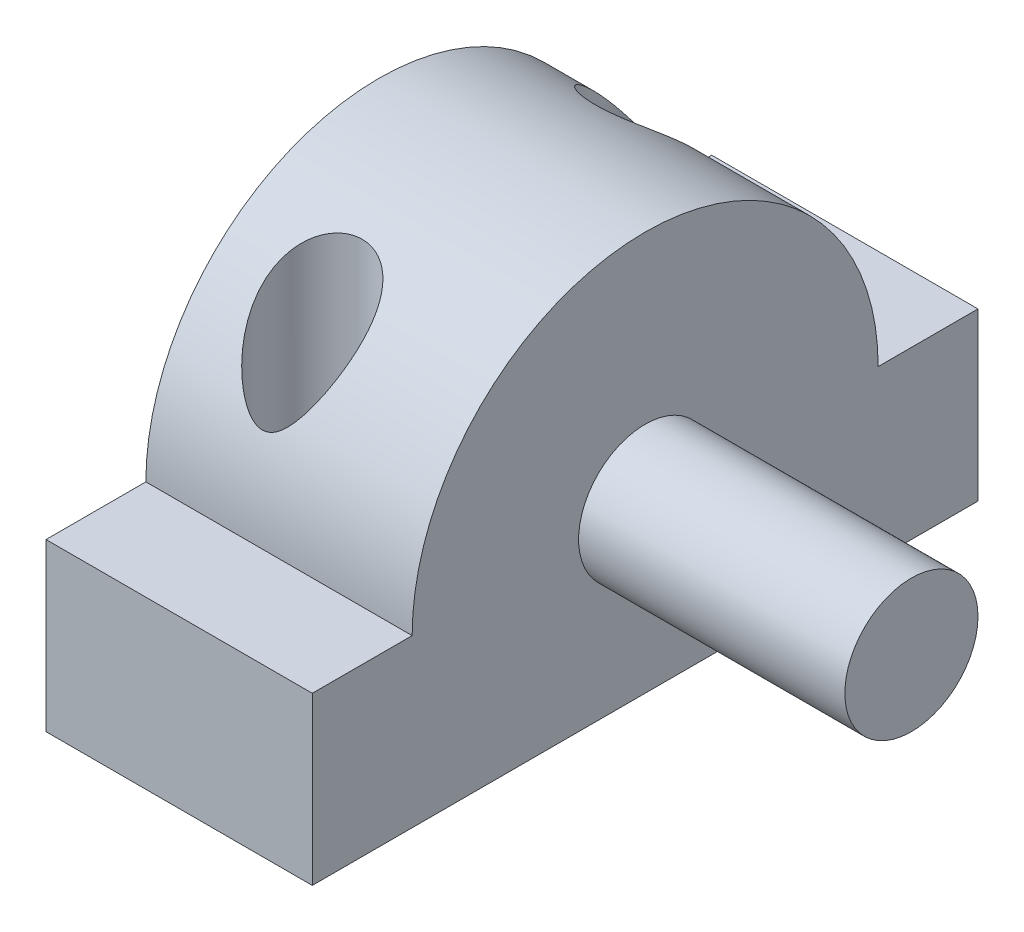
SolidWorks part; units mm, degrees
ref_plane "Front Plane" through (0, 0, 0) normal (0, 0, 1) x (1, 0, 0)
ref_plane "Top Plane" through (0, 0, 0) normal (0, 1, 0) x (1, 0, 0)
ref_plane "Right Plane" through (0, 0, 0) normal (1, 0, 0) x (0, 0, -1)
sketch "Sketch1" plane through (0, 0, 0) normal (1, 0, 0) x (0, 0, -1)
  line L0 (17, 0) -> (20, 0)
  line L1 (0, 0) -> (3, 0)
  line L2 (0, 0) -> (0, -5)
  line L3 (0, -5) -> (20, -5)
  line L4 (20, 0) -> (20, -5)
  arc A1 (17, 0) -> (3, 0) centre (10, 0) ccw
  dimension "D1" = 5
  dimension "D4" = 7
  dimension "D2" = 20
  dimension "D3" = 10
extrude "Boss-Extrude1" add sketch "Sketch1" along normal blind 8
sketch "Sketch2" plane through (8, 0, 0) normal (1, 0, 0) x (0, 0, -1)
  circle A0 centre (10, 0) radius 2
  dimension "D1" = 4
extrude "Boss-Extrude2" add sketch "Sketch2" along normal blind 8
sketch "Sketch3" plane through (0, -5, 0) normal (0, -1, 0) x (1, 0, 0)
  line L0 (0, -10) -> (8, -10) construction
  line L1 (0, 0) -> (0, -20) construction
  line L2 (8, 0) -> (8, -20) construction
  circle A0 centre (3, -5) radius 1.5
  circle A1 centre (3, -15) radius 1.5
  dimension "D1" = 3
  dimension "D2" = 3
  dimension "D3" = 5
extrude "Cut-Extrude1" cut sketch "Sketch3" against normal blind 15
